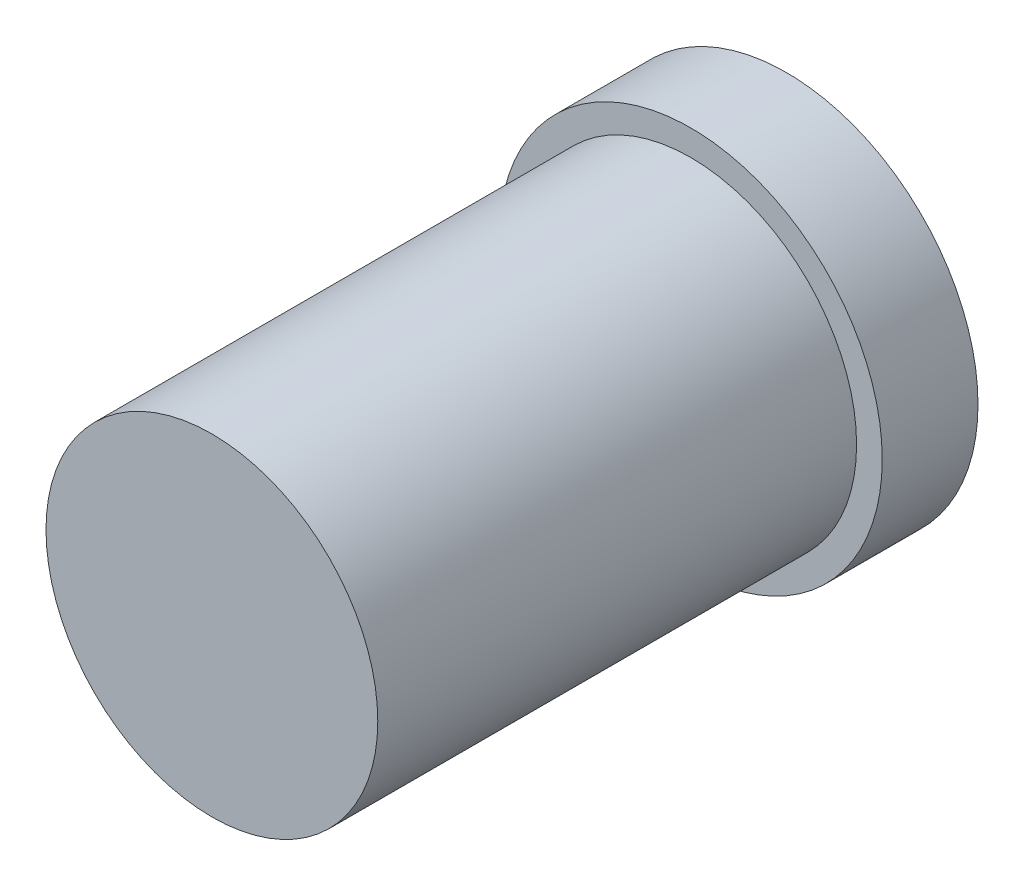
SolidWorks part; units mm, degrees
ref_plane "Front" through (0, 0, 0) normal (0, 0, 1) x (1, 0, 0)
ref_plane "Top" through (0, 0, 0) normal (0, 1, 0) x (1, 0, 0)
ref_plane "Right" through (0, 0, 0) normal (1, 0, 0) x (0, 0, -1)
sketch "Sketch1" plane through (0, 0, 0) normal (0, 0, 1) x (1, 0, 0)
  circle A0 centre (0, 0) radius 82.4992
  dimension "D1" = 164.9984
extrude "Boss-Extrude1" add sketch "Sketch1" against normal blind 285.75
sketch "Sketch2" plane through (0, 0, -285.75) normal (0, 0, -1) x (-1, 0, 0)
  circle A0 centre (0, 0) radius 95.25
  dimension "D1" = 190.5
extrude "Boss-Extrude2" add sketch "Sketch2" against normal blind 47.625
